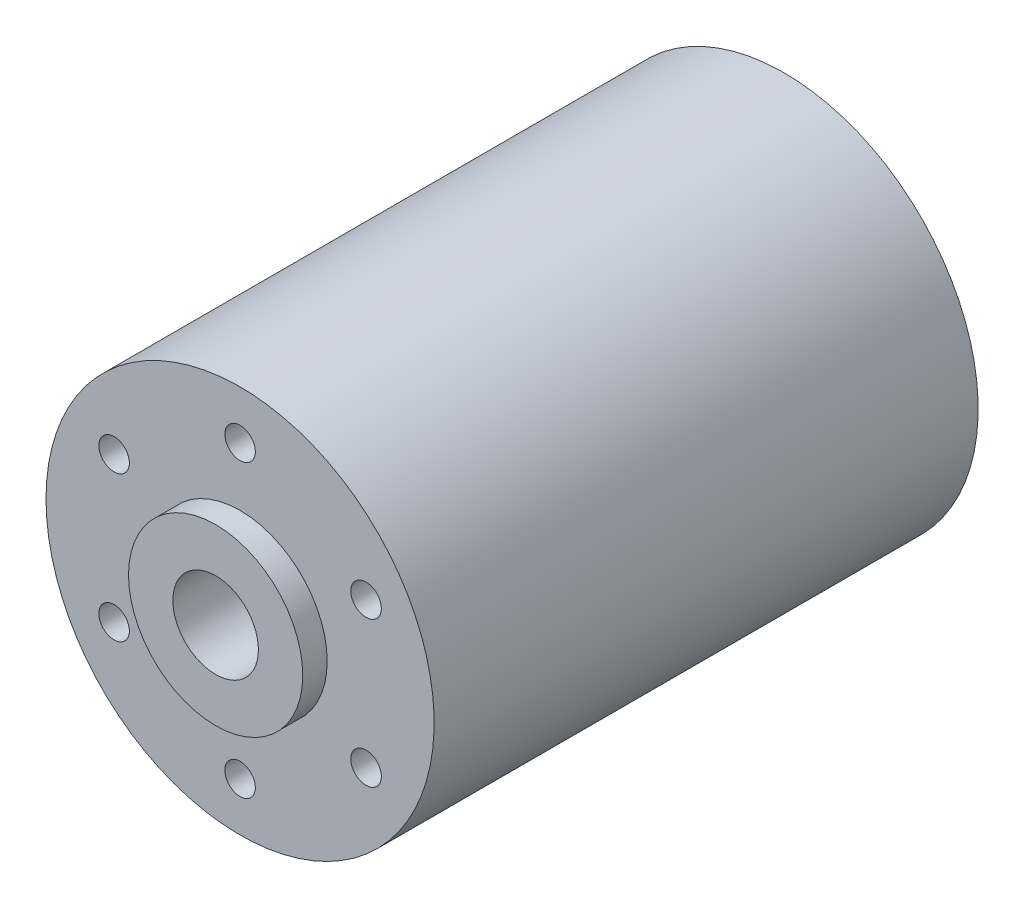
SolidWorks part; units mm, degrees
material "Nailon 101"
ref_plane "Alzado" through (0, 0, 0) normal (0, 0, 1) x (1, 0, 0)
ref_plane "Planta" through (0, 0, 0) normal (0, 1, 0) x (1, 0, 0)
ref_plane "Vista lateral" through (0, 0, 0) normal (1, 0, 0) x (0, 0, -1)
sketch "Croquis3" plane through (0, 0, 0) normal (0, 0, 1) x (1, 0, 0)
  circle A0 centre (0, 0) radius 31.75
  dimension "D1" = 63.5
extrude "Saliente-Extruir3" add sketch "Croquis3" along normal blind 97
sketch "Croquis4" plane through (0, 0, 97) normal (0, 0, 1) x (1, 0, 0)
  circle A4 centre (0, 0) radius 7
  dimension "D1" = 14
extrude "Cortar-Extruir1" cut sketch "Croquis4" against normal through all
sketch "Croquis8" plane through (0, 0, 97) normal (0, 0, 1) x (1, 0, 0)
  circle A0 centre (0, 23.8) radius 2.5
  circle A2 centre (0, 0) radius 14.3 construction
  dimension "D1" = 5
  dimension "D3" = 23.8
extrude "Cortar-Extruir6" cut sketch "Croquis8" against normal through all
pattern_circular "MatrizC1" count 6 over 360 about axis through (0, 0, 0) along (0, 0, 1) of "Cortar-Extruir6"
ref_plane "Plano1" through (0, 0, 48.5) normal (0, 0, 1) x (1, 0, 0)
sketch "Sketch1" plane through (0, 0, 97) normal (0, 0, 1) x (1, 0, 0)
  circle A0 centre (0, 0) radius 14.25
  circle A2 centre (0, 0) radius 31.75 construction
  circle A3 centre (0, 0) radius 31.75
  dimension "D1" = 28.5
extrude "Cut-Extrude1" cut sketch "Sketch1" against normal blind 4
ref_plane "Plane1" through (0, 0, 48.5) normal (0, 0, 1) x (1, 0, 0)
mirror "Mirror1" about plane through (0, 0, 48.5) normal (0, 0, 1) of "Cut-Extrude1"
